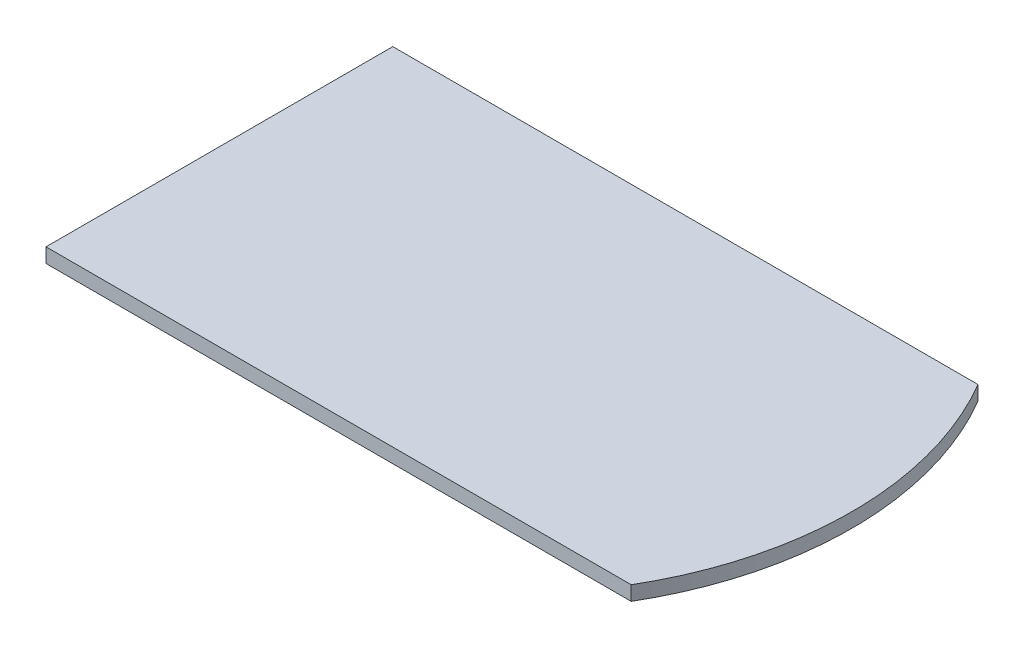
SolidWorks part; units mm, degrees
ref_plane "Front Plane" through (0, 0, 0) normal (0, 0, 1) x (1, 0, 0)
ref_plane "Top Plane" through (0, 0, 0) normal (0, 1, 0) x (1, 0, 0)
ref_plane "Right Plane" through (0, 0, 0) normal (1, 0, 0) x (0, 0, -1)
sketch "Sketch1" plane through (0, 0, 0) normal (0, 1, 0) x (1, 0, 0)
  line L1 (0, 0) -> (162, 0)
  line L2 (0, 0) -> (0, -96)
  line L3 (0, -96) -> (162, -96)
  line L4 (162, 0) -> (162, -96)
  arc A0 (162, -96) -> (162, 0) centre (80.2288, -48) ccw
  dimension "D1" = 162
  dimension "D2" = 96
extrude "Boss-Extrude1" add sketch "Sketch1" along normal blind 4
